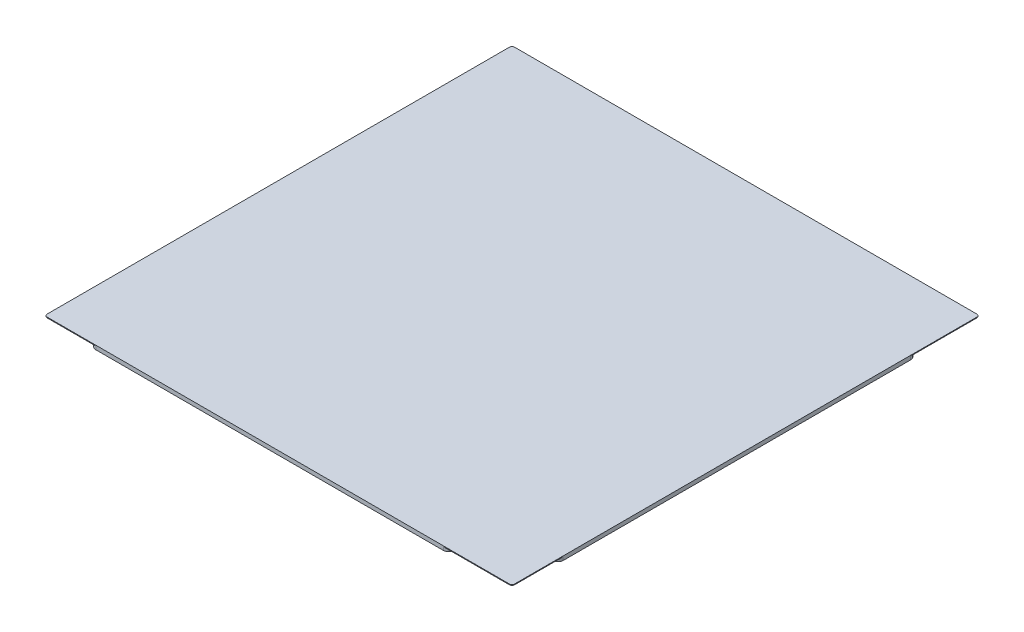
SolidWorks part; units mm, degrees
material "Kapton"
ref_plane "Front Plane" through (0, 0, 0) normal (0, 0, 1) x (1, 0, 0)
ref_plane "Top Plane" through (0, 0, 0) normal (0, 1, 0) x (1, 0, 0)
ref_plane "Right Plane" through (0, 0, 0) normal (1, 0, 0) x (0, 0, -1)
sketch "Sketch1" plane through (0, 0, 0) normal (0, 1, 0) x (1, 0, 0)
  line L1 (-93.5, -93.5) -> (93.5, -93.5)
  line L2 (-93.5, -93.5) -> (-93.5, 93.5)
  line L3 (-93.5, 93.5) -> (93.5, 93.5)
  line L4 (93.5, -93.5) -> (93.5, 93.5)
  line L5 (-93.5, -93.5) -> (93.5, 93.5) construction
  line L6 (-93.5, 93.5) -> (93.5, -93.5) construction
  point P0 (0, 0)
  dimension "D1" = 187
extrude "Boss-Extrude1" add sketch "Sketch1" along normal mid plane 0.3
sketch "Sketch2" plane through (0, -0.15, 0) normal (0, -1, 0) x (1, 0, 0)
  line L0 (95, -93.5) -> (65, -93.5) construction
  line L1 (93.5, -93.5) -> (-93.5, -93.5) construction
  line L2 (65, -93.5) -> (15, -93.5) construction
  line L3 (15, -93.5) -> (-15, -93.5) construction
  line L4 (-15, -93.5) -> (-65, -93.5) construction
  line L5 (-65, -93.5) -> (-95, -93.5) construction
  line L6 (65, -93.5) -> (75, -80) construction
  line L7 (-93.5, -93.5) -> (-93.5, 93.5) construction
  line L8 (93.5, 93.5) -> (93.5, -93.5) construction
  line L9 (-80, -75) -> (-93.5, -75)
  line L10 (75, -80) -> (-68, -80)
  line L11 (75, -80) -> (75, -93.5)
  line L12 (75, -93.5) -> (-68, -93.5)
  line L13 (-68, -80) -> (-68, -93.5)
  line L14 (-80, -75) -> (-80, 68)
  line L15 (-80, 68) -> (-93.5, 68)
  line L16 (-93.5, -75) -> (-93.5, 68)
  line L17 (-75, 80) -> (-75, 93.5)
  line L18 (-75, 80) -> (68, 80)
  line L19 (68, 80) -> (68, 93.5)
  line L20 (-75, 93.5) -> (68, 93.5)
  line L21 (80, 75) -> (93.5, 75)
  line L22 (80, 75) -> (80, -68)
  line L23 (80, -68) -> (93.5, -68)
  line L24 (93.5, 75) -> (93.5, -68)
  line L25 (-93.5, 93.5) -> (93.5, 93.5) construction
  point P33 (0, 0)
  dimension "D1" = 50
  dimension "D2" = 13.5
  dimension "D3" = 10
  dimension "D4" = 1.5
  dimension "D5" = 1.5
  dimension "D6" = 3
  dimension "D7" = 4
extrude "Boss-Extrude2" add sketch "Sketch2" along normal blind 1.3
fillet "Fillet1" radius 2 16 edges at (75, -0.8, -80) (-68, -0.8, -80) (-68, -0.8, -93.5) (-93.5, -0.8, -75) (-80, -0.8, -75) (-80, -0.8, 68) (-93.5, -0.8, 68) (-75, -0.8, 93.5) (-75, -0.8, 80) (68, -0.8, 80) (68, -0.8, 93.5) (75, -0.8, -93.5) (80, -0.8, 75) (93.5, -0.8, 75) (93.5, -0.8, -68) (80, -0.8, -68)
fillet "Fillet2" radius 1 4 edges at (-93.5, 0, 93.5) (-93.5, 0, -93.5) (93.5, 0, -93.5) (93.5, 0, 93.5)
equation "\"panel_width\"= 190mm"
equation "\"finger_joint_width\" = 50mm"
equation "\"D1@Sketch1\"=\"panel_width\"-3"
equation "\"D1@Sketch2\"=\"finger_joint_width\""
